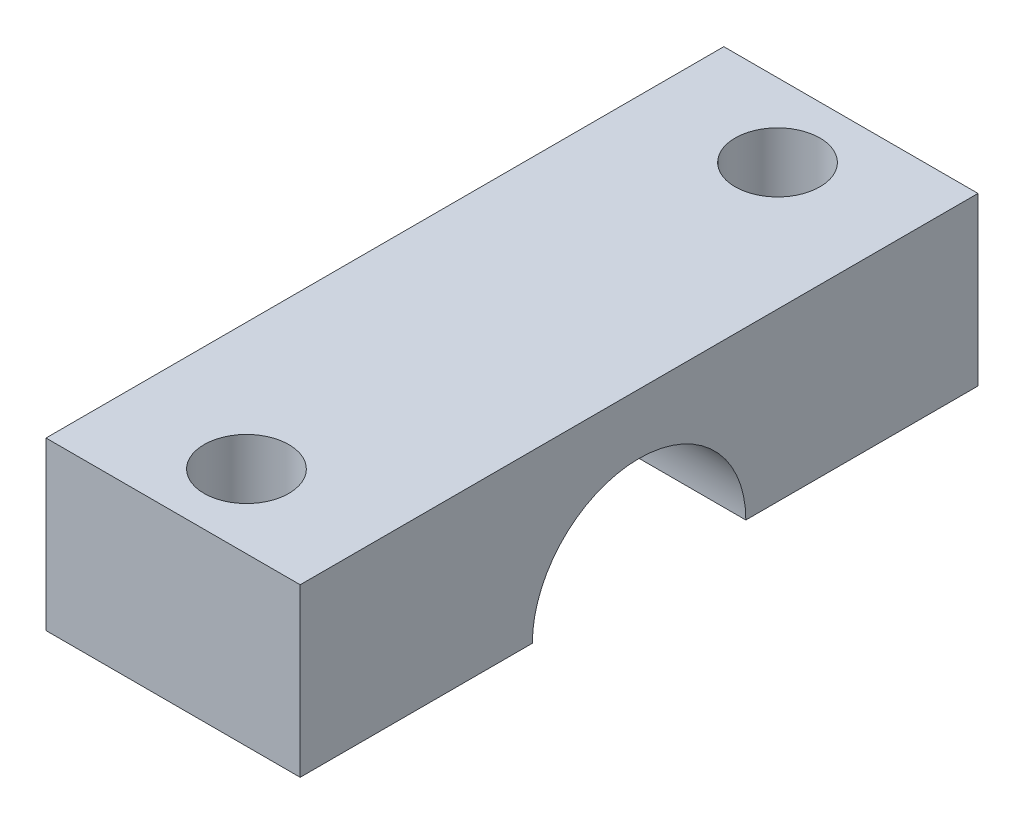
SolidWorks part; units mm, degrees
ref_plane "Front Plane" through (0, 0, 0) normal (0, 0, 1) x (1, 0, 0)
ref_plane "Top Plane" through (0, 0, 0) normal (0, 1, 0) x (1, 0, 0)
ref_plane "Right Plane" through (0, 0, 0) normal (1, 0, 0) x (0, 0, -1)
sketch "Sketch1" plane through (0, 0, 0) normal (1, 0, 0) x (0, 0, -1)
  line L0 (-4, 0) -> (-12.7, 0)
  line L1 (12.7, 6.25) -> (-12.7, 6.25)
  line L2 (12.7, 6.25) -> (12.7, 0)
  line L3 (12.7, 0) -> (4, 0)
  line L4 (-12.7, 6.25) -> (-12.7, 0)
  arc A0 (4, 0) -> (-4, 0) centre (0, 0) ccw
  dimension "D1" = 8
  dimension "D2" = 0
  dimension "D3" = 25.4
  dimension "D4" = 12.7
  dimension "D5" = 6.25
extrude "Boss-Extrude1" add sketch "Sketch1" along normal blind 9.525
sketch "Sketch2" plane through (0, 6.25, 0) normal (0, 1, 0) x (1, 0, 0)
  line L0 (9.525, -12.7) -> (0, -12.7) construction
  line L1 (9.525, 12.7) -> (9.525, -12.7) construction
  line L2 (9.525, 12.7) -> (0, 12.7) construction
  circle A0 centre (4.7625, -9.95) radius 1.5875
  circle A1 centre (4.7625, 9.95) radius 1.5875
  dimension "D1" = 3.175
  dimension "D4" = 3.175
  dimension "D2" = 2.75
  dimension "D3" = 4.7625
  dimension "D5" = 2.75
  dimension "D6" = 4.7625
extrude "Cut-Extrude1" cut sketch "Sketch2" against normal through all
equation "\"D4@Sketch1\"=\"D3@Sketch1\"/2"
equation "\"D5@Sketch2\"=\"D2@Sketch2\""
equation "\"D4@Sketch2\"=\"D1@Sketch2\""
equation "\"D6@Sketch2\"=\"D3@Sketch2\""
